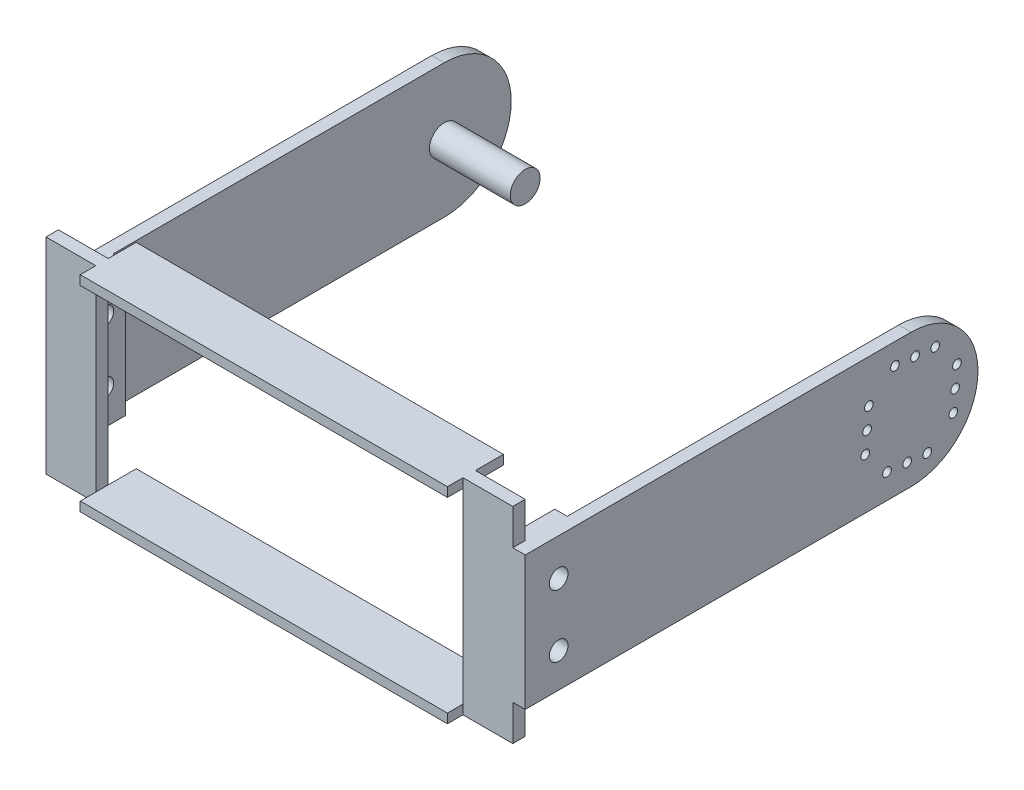
SolidWorks part; units mm, degrees
ref_plane "정면" through (0, 0, 0) normal (0, 0, 1) x (1, 0, 0)
ref_plane "윗면" through (0, 0, 0) normal (0, 1, 0) x (1, 0, 0)
ref_plane "우측면" through (0, 0, 0) normal (1, 0, 0) x (0, 0, -1)
ref_plane "평면4" through (62.3829, 0, 0) normal (1, 0, 0) x (0, 0, -1)
sketch "스케치2" plane through (62.3829, 0, 0) normal (1, 0, 0) x (0, 0, -1)
  circle A0 centre (-61.8032, 76.4477) radius 0.5 construction
  circle A1 centre (-65.6774, 69.6681) radius 10.75
  circle A2 centre (-65.6774, 69.6681) radius 10.75
  circle A3 centre (-65.0401, 76.7394) radius 0.5 construction
  circle A4 centre (-68.277, 77.0312) radius 0.5 construction
  circle A5 centre (-72.457, 73.5423) radius 0.5 construction
  circle A6 centre (-72.7488, 70.3054) radius 0.5 construction
  circle A7 centre (-73.0405, 67.0685) radius 0.5 construction
  circle A8 centre (-69.5516, 62.8885) radius 0.5 construction
  circle A9 centre (-66.3147, 62.5968) radius 0.5 construction
  circle A10 centre (-63.0778, 62.305) radius 0.5 construction
  circle A11 centre (-58.8978, 65.7939) radius 0.5 construction
  circle A12 centre (-58.6061, 69.0308) radius 0.5 construction
  circle A13 centre (-58.3144, 72.2677) radius 0.5 construction
  circle A14 centre (-61.8032, 76.4477) radius 0.5
  circle A15 centre (-65.0401, 76.7394) radius 0.5
  circle A16 centre (-68.277, 77.0312) radius 0.5
  circle A17 centre (-72.457, 73.5423) radius 0.5
  circle A18 centre (-72.7488, 70.3054) radius 0.5
  circle A19 centre (-73.0405, 67.0685) radius 0.5
  circle A20 centre (-69.5516, 62.8885) radius 0.5
  circle A21 centre (-66.3147, 62.5968) radius 0.5
  circle A22 centre (-63.0778, 62.305) radius 0.5
  circle A23 centre (-58.8978, 65.7939) radius 0.5
  circle A24 centre (-58.6061, 69.0308) radius 0.5
  circle A25 centre (-58.3144, 72.2677) radius 0.5
  dimension "D1" = 0
extrude "보스-돌출1" add sketch "스케치2" along normal blind 2
sketch "스케치3" plane through (62.3829, 0, 0) normal (-1, 0, 0) x (0, 0, 1)
  line L0 (65.6774, 80.4181) -> (65.6774, 58.9181) construction
  line L1 (65.6774, 80.4181) -> (127.6774, 80.4181)
  line L3 (65.6774, 58.9181) -> (127.6774, 58.9181)
  line L4 (127.6774, 80.4181) -> (127.6774, 58.9181)
  circle A0 centre (65.6774, 69.6681) radius 10.75 construction
  arc A1 (65.6774, 58.9181) -> (65.6774, 80.4181) centre (65.6774, 69.6681) ccw
  dimension "D1" = 62
  dimension "D2" = 21.5
extrude "보스-돌출3" add sketch "스케치3" against normal blind 2
sketch "스케치4" plane through (62.3829, 0, 0) normal (-1, 0, 0) x (0, 0, 1)
  line L1 (127.6774, 58.9181) -> (127.6774, 80.4181) construction
  line L2 (127.6774, 86.1681) -> (125.6774, 86.1681)
  line L3 (127.6774, 86.1681) -> (127.6774, 53.1681)
  line L4 (127.6774, 53.1681) -> (125.6774, 53.1681)
  line L5 (125.6774, 86.1681) -> (125.6774, 53.1681)
  point P8 (127.6774, 69.6681)
  dimension "D1" = 2
  dimension "D2" = 33
extrude "보스-돌출4" add sketch "스케치4" along normal blind 75
sketch "스케치8" plane through (64.3829, 0, 0) normal (1, 0, 0) x (0, 0, -1)
  circle A0 centre (-72.457, 73.5423) radius 0.5 construction
  circle A1 centre (-72.7488, 70.3054) radius 0.5 construction
  circle A2 centre (-73.0405, 67.0685) radius 0.5 construction
  circle A3 centre (-69.5516, 62.8885) radius 0.5 construction
  circle A4 centre (-66.3147, 62.5968) radius 0.5 construction
  circle A5 centre (-63.0778, 62.305) radius 0.5 construction
  circle A6 centre (-58.8978, 65.7939) radius 0.5 construction
  circle A7 centre (-58.6061, 69.0308) radius 0.5 construction
  circle A8 centre (-58.3144, 72.2677) radius 0.5 construction
  circle A9 centre (-61.8032, 76.4477) radius 0.5 construction
  circle A10 centre (-65.0401, 76.7394) radius 0.5 construction
  circle A11 centre (-68.277, 77.0312) radius 0.5 construction
  circle A24 centre (-68.277, 77.0312) radius 0.5 construction
  circle A25 centre (-65.0401, 76.7394) radius 0.5 construction
  circle A26 centre (-61.8032, 76.4477) radius 0.5 construction
  circle A27 centre (-58.3144, 72.2677) radius 0.5 construction
  circle A28 centre (-58.6061, 69.0308) radius 0.5 construction
  circle A29 centre (-58.8978, 65.7939) radius 0.5 construction
  circle A30 centre (-63.0778, 62.305) radius 0.5 construction
  circle A31 centre (-66.3147, 62.5968) radius 0.5 construction
  circle A32 centre (-69.5516, 62.8885) radius 0.5 construction
  circle A33 centre (-73.0405, 67.0685) radius 0.5 construction
  circle A34 centre (-72.7488, 70.3054) radius 0.5 construction
  circle A35 centre (-72.457, 73.5423) radius 0.5 construction
  circle A36 centre (-68.277, 77.0312) radius 0.7
  circle A37 centre (-65.0401, 76.7394) radius 0.7
  circle A38 centre (-61.8032, 76.4477) radius 0.7
  circle A39 centre (-58.3144, 72.2677) radius 0.7
  circle A40 centre (-58.6061, 69.0308) radius 0.7
  circle A41 centre (-58.8978, 65.7939) radius 0.7
  circle A42 centre (-63.0778, 62.305) radius 0.7
  circle A43 centre (-66.3147, 62.5968) radius 0.7
  circle A44 centre (-69.5516, 62.8885) radius 0.7
  circle A45 centre (-73.0405, 67.0685) radius 0.7
  circle A46 centre (-72.7488, 70.3054) radius 0.7
  circle A47 centre (-72.457, 73.5423) radius 0.7
  dimension "D1" = 0.2
extrude "컷-돌출1" cut sketch "스케치8" against normal blind 7
sketch "스케치9" plane through (0, 0, 125.6774) normal (0, 0, -1) x (-1, 0, 0)
  line L0 (12.6171, 86.1681) -> (12.6171, 53.1681) construction
  line L1 (12.6171, 80.4181) -> (10.6171, 80.4181)
  line L2 (12.6171, 80.4181) -> (12.6171, 58.9181)
  line L3 (12.6171, 58.9181) -> (10.6171, 58.9181)
  line L4 (10.6171, 80.4181) -> (10.6171, 58.9181)
  point P6 (12.6171, 69.6681)
  dimension "D1" = 2
  dimension "D2" = 21.5
extrude "보스-돌출7" add sketch "스케치9" along normal blind 60
sketch "스케치10" plane through (-12.6171, 0, 0) normal (-1, 0, 0) x (0, 0, 1)
  line L0 (65.6774, 80.4181) -> (65.6774, 58.9181) construction
  arc A0 (65.6774, 80.4181) -> (65.6774, 58.9181) centre (65.6774, 69.6681) ccw
extrude "돌출-얇게2" add sketch "스케치10" against normal blind 2 thin thin type one direction reverse wall 10
sketch "스케치11" plane through (-12.6171, 0, 0) normal (-1, 0, 0) x (0, 0, 1)
  line L0 (65.6774, 68.9181) -> (65.6774, 70.4181) construction
  circle A0 centre (65.6774, 69.6681) radius 2.4
  dimension "D1" = 4.8
extrude "보스-돌출8" add sketch "스케치11" against normal blind 15
sketch "스케치12" plane through (0, 0, 127.6774) normal (0, 0, 1) x (1, 0, 0)
  line L0 (-12.6171, 69.6681) -> (64.3829, 69.6681) construction
  line L1 (-12.6171, 53.1681) -> (-12.6171, 86.1681) construction
  line L2 (64.3829, 58.9181) -> (64.3829, 80.4181) construction
  line L3 (24.8829, 86.1681) -> (24.8829, 53.1681) construction
  line L4 (-12.6171, 86.1681) -> (62.3829, 86.1681) construction
  line L5 (-12.6171, 53.1681) -> (62.3829, 53.1681) construction
  line L7 (-4.6171, 84.6681) -> (54.3829, 84.6681)
  line L8 (-4.6171, 84.6681) -> (-4.6171, 54.6681)
  line L9 (-4.6171, 54.6681) -> (54.3829, 54.6681)
  line L10 (54.3829, 84.6681) -> (54.3829, 54.6681)
  line L11 (-4.6171, 84.6681) -> (54.3829, 54.6681) construction
  line L12 (-4.6171, 54.6681) -> (54.3829, 84.6681) construction
  point P12 (24.8829, 69.6681)
  dimension "D1" = 59
  dimension "D2" = 30
extrude "컷-돌출2" cut sketch "스케치12" against normal blind 15
sketch "스케치13" plane through (0, 0, 125.6774) normal (0, 0, -1) x (-1, 0, 0)
  line L0 (-24.8829, 86.1681) -> (-24.8829, 53.1681) construction
  line L1 (12.6171, 86.1681) -> (-62.3829, 86.1681) construction
  line L2 (12.6171, 53.1681) -> (-62.3829, 53.1681) construction
  line L4 (-54.3829, 54.6681) -> (4.6171, 54.6681)
  line L5 (-54.3829, 54.6681) -> (-54.3829, 53.1681)
  line L6 (-54.3829, 53.1681) -> (4.6171, 53.1681)
  line L7 (4.6171, 54.6681) -> (4.6171, 53.1681)
  line L8 (-54.3829, 54.6681) -> (4.6171, 53.1681) construction
  line L9 (-54.3829, 53.1681) -> (4.6171, 54.6681) construction
  line L11 (4.6171, 54.6681) -> (4.6171, 53.1681) construction
  line L14 (-54.3829, 69.6681) -> (12.6171, 69.6681) construction
  line L15 (-54.3829, 54.6681) -> (-54.3829, 84.6681) construction
  line L16 (12.6171, 58.9181) -> (12.6171, 80.4181) construction
  line L17 (4.6171, 84.6681) -> (4.6171, 86.1681)
  line L18 (-54.3829, 86.1681) -> (4.6171, 86.1681)
  line L19 (-54.3829, 84.6681) -> (-54.3829, 86.1681)
  line L20 (-54.3829, 84.6681) -> (4.6171, 84.6681)
  point P6 (-24.8829, 53.9181)
  dimension "D1" = 1.5
  dimension "D2" = 1.5
  dimension "D3" = 59
extrude "보스-돌출9" add sketch "스케치13" along normal mid plane 9
sketch "스케치15" plane through (62.3829, 0, 0) normal (-1, 0, 0) x (0, 0, 1)
  line L1 (118.9279, 80.4181) -> (125.6774, 80.4181)
  line L2 (118.9279, 80.4181) -> (118.9279, 58.9181)
  line L3 (118.9279, 58.9181) -> (125.6774, 58.9181)
  line L4 (125.6774, 80.4181) -> (125.6774, 58.9181)
  line L5 (125.6774, 80.4181) -> (125.6774, 58.9181) construction
  line L6 (125.6774, 80.4181) -> (65.6774, 80.4181) construction
  line L7 (65.6774, 58.9181) -> (125.6774, 58.9181) construction
extrude "보스-돌출10" add sketch "스케치15" along normal blind 2
sketch "스케치16" plane through (-10.6171, 0, 0) normal (1, 0, 0) x (0, 0, -1)
  line L7 (-118.9279, 58.9181) -> (-118.9279, 80.4181)
  line L8 (-125.6774, 58.9181) -> (-118.9279, 58.9181)
  line L9 (-125.6774, 80.4181) -> (-125.6774, 58.9181)
  line L10 (-118.9279, 80.4181) -> (-125.6774, 80.4181)
  line L11 (-118.9279, 58.9181) -> (-118.9279, 80.4181)
  line L12 (-125.6774, 58.9181) -> (-118.9279, 58.9181)
  line L13 (-125.6774, 80.4181) -> (-125.6774, 58.9181)
  line L14 (-118.9279, 80.4181) -> (-125.6774, 80.4181)
  dimension "D1" = 0
extrude "보스-돌출11" add sketch "스케치16" along normal blind 2
sketch "스케치17" plane through (60.3829, 0, 0) normal (-1, 0, 0) x (0, 0, 1)
  line L0 (122.3026, 80.4181) -> (122.3026, 58.9181) construction
  line L4 (118.9279, 80.4181) -> (118.9279, 58.9181)
  line L5 (118.9279, 58.9181) -> (125.6774, 58.9181)
  line L6 (125.6774, 58.9181) -> (125.6774, 80.4181)
  line L7 (125.6774, 80.4181) -> (118.9279, 80.4181)
  line L8 (118.9279, 80.4181) -> (118.9279, 58.9181) construction
  line L9 (118.9279, 58.9181) -> (125.6774, 58.9181) construction
  line L10 (125.6774, 58.9181) -> (125.6774, 80.4181) construction
  line L11 (125.6774, 80.4181) -> (118.9279, 80.4181) construction
  circle A0 centre (122.3026, 74.4374) radius 1.5
  circle A1 centre (122.3026, 64.4219) radius 1.5
  dimension "D2" = 3
  dimension "D3" = 3
  dimension "D1" = 0
extrude "컷-돌출3" cut sketch "스케치17" against normal through all and the other way through all
